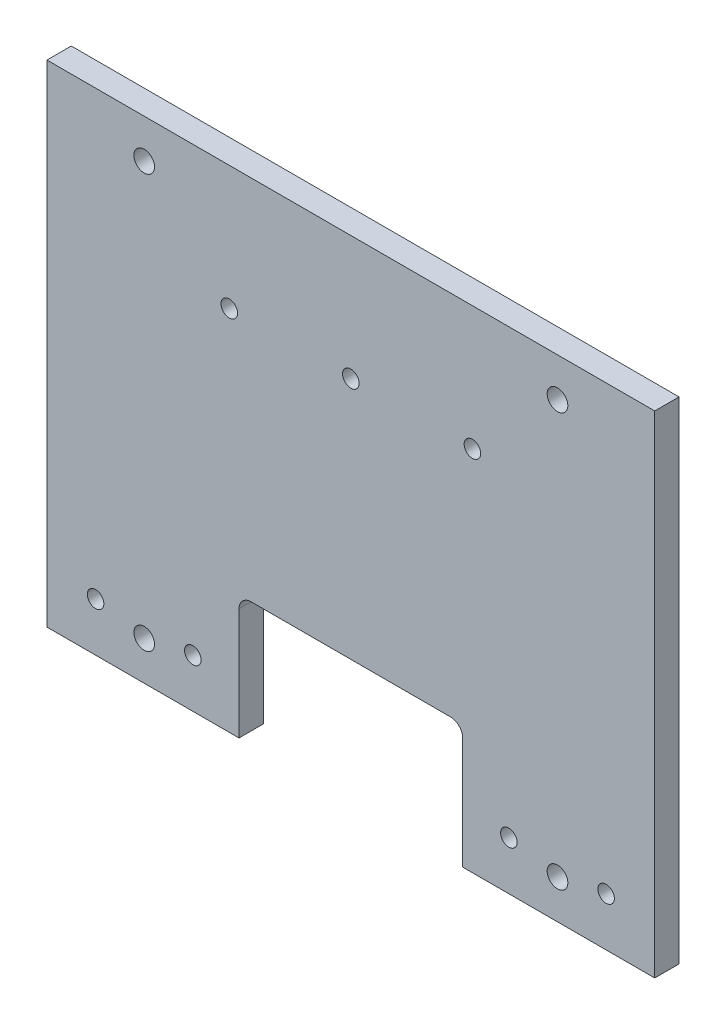
SolidWorks part; units mm, degrees
material "A6061"
ref_plane "前视基准面" through (0, 0, 0) normal (0, 0, 1) x (1, 0, 0)
ref_plane "上视基准面" through (0, 0, 0) normal (0, 1, 0) x (1, 0, 0)
ref_plane "右视基准面" through (0, 0, 0) normal (1, 0, 0) x (0, 0, -1)
sketch "草图1" plane through (0, 0, 0) normal (0, 0, 1) x (1, 0, 0)
  line L0 (0, 315.2001) -> (0, -427.8207) construction
  line L1 (125, 101) -> (-125, 101)
  line L2 (125, 101) -> (125, -101)
  line L3 (125, -101) -> (-125, -101)
  line L4 (-125, 101) -> (-125, -101)
  line L5 (125, 101) -> (-125, -101) construction
  line L6 (125, -101) -> (-125, 101) construction
  line L7 (-372.8838, 0) -> (367.3901, 0) construction
  line L9 (41, -50) -> (-41, -50)
  line L10 (46, -55) -> (46, -167.8812)
  line L11 (46, -167.8812) -> (-46, -167.8812)
  line L12 (-46, -55) -> (-46, -167.8812)
  line L13 (46, -50) -> (-46, -167.8812) construction
  line L14 (46, -167.8812) -> (-46, -50) construction
  circle A0 centre (-85, 85) radius 4
  circle A1 centre (85, 85) radius 4
  circle A2 centre (85, -85) radius 4
  circle A3 centre (-85, -85) radius 4
  arc A4 (41, -50) -> (46, -55) centre (41, -55) cw
  arc A5 (-41, -50) -> (-46, -55) centre (-41, -55) ccw
  point P0 (0, 0)
  point P18 (0, -108.9406)
  dimension "D1" = 170
  dimension "D2" = 170
  dimension "D3" = 8
  dimension "D8" = 5
  dimension "D4" = 202
  dimension "D5" = 250
  dimension "D6" = 92
  dimension "D7" = 50
extrude "凸台-拉伸1" add sketch "草图1" along normal blind 10 contours L12 L9 L10 L3 L2 L1 L4 A1 A0 A2 A3
hole_wizard "M10 螺纹孔1" positions "草图3" profile "草图4" tap size "M10" standard "GB" end condition through all
sketch "草图3" plane through (0, 0, 10) normal (0, 0, 1) x (1, 0, 0)
  point P0 (85, -85)
  point P3 (-85, -85)
  point P6 (-85, 85)
  point P9 (85, 85)
sketch "草图4" plane through (85, -85, 10) normal (1, 0, 0) x (0, -1, 0)
  line L0 (0, 0) -> (0, 10)
  line L1 (0, 10) -> (4.25, 10)
  line L2 (4.25, 10) -> (4.25, 0)
  line L5 (4.25, 0) -> (0, 0)
  line L11 (0, -6.35) -> (0, 107.95) construction
  dimension "通孔螺纹孔钻头直径" = 8.5
  dimension "通孔螺纹孔钻头深度" = 10
cosmetic thread "孔螺蚊线1" parameters "D2"=10
cosmetic thread "孔螺蚊线2" parameters "D2"=10
cosmetic thread "孔螺蚊线3" parameters "D2"=10
cosmetic thread "孔螺蚊线4" parameters "D2"=10
sketch "草图5" plane through (0, 0, 0) normal (0, 0, -1) x (-1, 0, 0)
  line L0 (0, 115.5213) -> (0, -114.3325) construction
  line L1 (-105, -81) -> (105, -81) construction
  line L4 (-125, -101) -> (-46, -101) construction
  line L5 (-85, -63.3892) -> (-85, -98.0928) construction
  line L6 (-125, 101) -> (125, 101) construction
  line L7 (-50, 50) -> (50, 50) construction
  circle A0 centre (-50, 50) radius 2.5
  circle A1 centre (-105, -81) radius 2.5
  circle A2 centre (-65, -81) radius 2.5
  circle A3 centre (50, 50) radius 2.5
  circle A4 centre (-85, -85) radius 1.5917 construction
  circle A5 centre (65, -81) radius 2.5
  circle A6 centre (105, -81) radius 2.5
  circle A7 centre (0, 50) radius 2.5
  dimension "D1" = 5
  dimension "D5" = 40
  dimension "D2" = 100
  dimension "D3" = 51
  dimension "D4" = 20
hole_wizard "M8 螺纹孔1" positions "草图7" profile "草图8" tap size "M8" standard "GB" end condition through all
sketch "草图7" plane through (0, 0, 0) normal (0, 0, -1) x (-1, 0, 0)
  point P0 (-50, 50)
  point P3 (0, 50)
  point P6 (50, 50)
  point P9 (-105, -81)
  point P12 (-65, -81)
  point P15 (65, -81)
  point P18 (105, -81)
sketch "草图8" plane through (50, 50, 0) normal (1, 0, 0) x (0, 1, 0)
  line L0 (0, 0) -> (0, 10)
  line L1 (0, 10) -> (3.4, 10)
  line L2 (3.4, 10) -> (3.4, 0)
  line L5 (3.4, 0) -> (0, 0)
  line L11 (0, -6.35) -> (0, 107.95) construction
  dimension "通孔螺纹孔钻头直径" = 6.8
  dimension "通孔螺纹孔钻头深度" = 10
cosmetic thread "孔螺蚊线5" parameters "D2"=8
cosmetic thread "孔螺蚊线6" parameters "D2"=8
cosmetic thread "孔螺蚊线7" parameters "D2"=8
cosmetic thread "孔螺蚊线8" parameters "D2"=8
cosmetic thread "孔螺蚊线9" parameters "D2"=8
cosmetic thread "孔螺蚊线10" parameters "D2"=8
cosmetic thread "孔螺蚊线11" parameters "D2"=8
